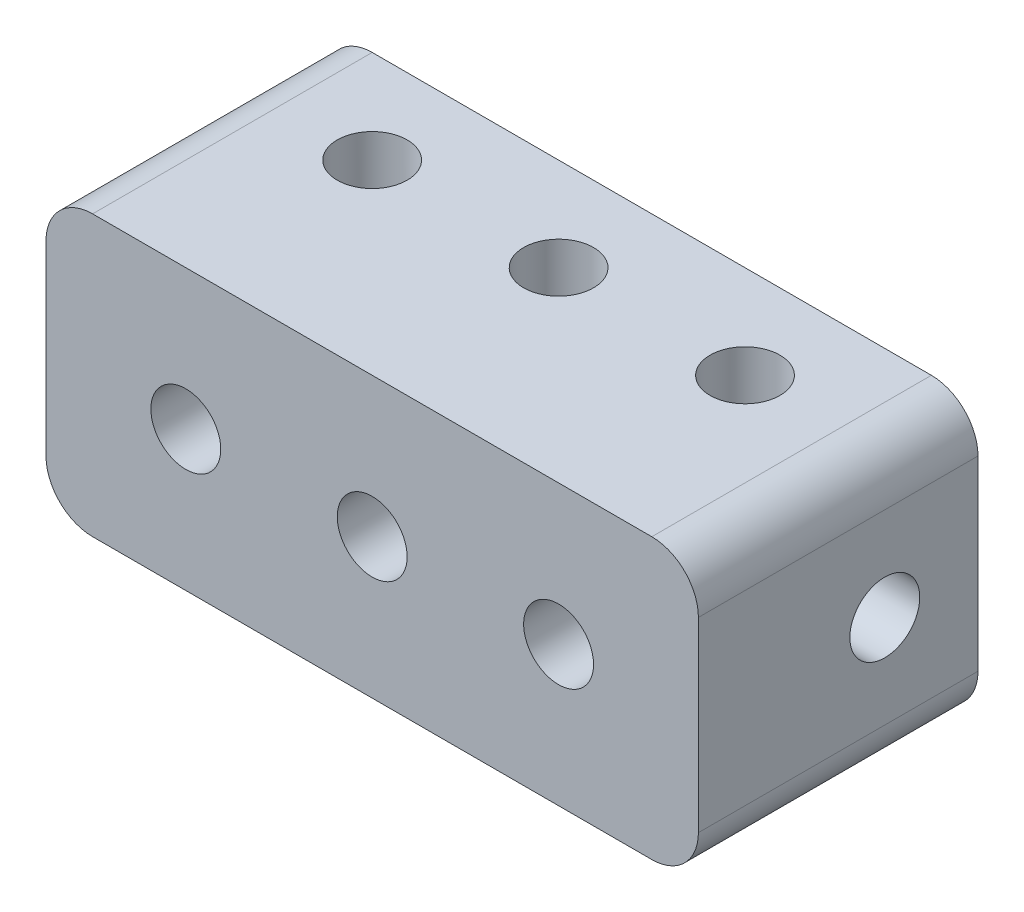
SolidWorks part; units mm, degrees
ref_plane "Front Plane" through (0, 0, 0) normal (0, 0, 1) x (1, 0, 0)
ref_plane "Top Plane" through (0, 0, 0) normal (0, 1, 0) x (1, 0, 0)
ref_plane "Right Plane" through (0, 0, 0) normal (1, 0, 0) x (0, 0, -1)
sketch "Sketch2" plane through (0, 0, 0) normal (0, 0, 1) x (1, 0, 0)
  line L1 (3.175, 0) -> (41.275, 0)
  line L2 (0, 3.175) -> (0, 15.875)
  line L3 (3.175, 19.05) -> (41.275, 19.05)
  line L4 (44.45, 3.175) -> (44.45, 15.875)
  arc A0 (0, 15.875) -> (3.175, 19.05) centre (3.175, 15.875) cw
  arc A1 (41.275, 19.05) -> (44.45, 15.875) centre (41.275, 15.875) cw
  arc A2 (3.175, 0) -> (0, 3.175) centre (3.175, 3.175) cw
  arc A3 (41.275, 0) -> (44.45, 3.175) centre (41.275, 3.175) ccw
  point P7 (0, 19.05)
  point P10 (44.45, 19.05)
  point P13 (0, 0)
  point P16 (44.45, 0)
  dimension "D3" = 3.175
  dimension "D4" = 3.175
  dimension "D5" = 3.175
  dimension "D6" = 3.175
  dimension "D1" = 44.45
  dimension "D2" = 19.05
extrude "Boss-Extrude1" add sketch "Sketch2" along normal blind 19.05
sketch "Sketch3" plane through (0, 0, 0) normal (0, 0, -1) x (-1, 0, 0)
  line L0 (-34.925, 9.525) -> (-9.525, 9.525) construction
  line L1 (-34.925, 14.2875) -> (-9.525, 14.2875)
  line L2 (-34.925, 4.7625) -> (-9.525, 4.7625)
  line L3 (-41.275, 19.05) -> (-3.175, 19.05) construction
  line L4 (-3.175, 0) -> (-41.275, 0) construction
  line L6 (0, 15.875) -> (0, 3.175) construction
  line L7 (-44.45, 3.175) -> (-44.45, 15.875) construction
  arc A0 (-34.925, 14.2875) -> (-34.925, 4.7625) centre (-34.925, 9.525) ccw
  arc A1 (-9.525, 4.7625) -> (-9.525, 14.2875) centre (-9.525, 9.525) ccw
  point P2 (-22.225, 9.525)
  dimension "D3" = 9.525
  dimension "D4" = 9.525
  dimension "D1" = 4.7625
  dimension "D2" = 4.7625
extrude "Cut-Extrude1" cut sketch "Sketch3" against normal blind 14.1224
sketch "Sketch4" plane through (0, 19.05, 0) normal (0, 1, 0) x (1, 0, 0)
  line L0 (44.45, -19.05) -> (44.45, 0) construction
  line L1 (41.275, -19.05) -> (3.175, -19.05) construction
  line L2 (0, -19.05) -> (0, 0) construction
  circle A0 centre (34.925, -6.35) radius 2.3812
  circle A1 centre (22.225, -6.35) radius 2.3813
  circle A2 centre (9.525, -6.35) radius 2.3812
  dimension "D1" = 9.525
  dimension "D2" = 12.7
  dimension "D3" = 4.7625
  dimension "D4" = 4.7625
  dimension "D5" = 4.7625
  dimension "D6" = 9.525
  dimension "D7" = 12.7
  dimension "D8" = 12.7
  dimension "D9" = 12.7
extrude "Cut-Extrude2" cut sketch "Sketch4" against normal through all both and the other way through all
sketch "Sketch5" plane through (44.45, 0, 0) normal (1, 0, 0) x (0, 0, -1)
  line L0 (0, 3.175) -> (0, 15.875) construction
  line L1 (-19.05, 0) -> (0, 0) construction
  circle A0 centre (-6.35, 9.525) radius 2.3813
  dimension "D1" = 6.35
  dimension "D2" = 4.7625
  dimension "D3" = 9.525
extrude "Cut-Extrude3" cut sketch "Sketch5" against normal through all both and the other way through all
sketch "Sketch7" plane through (0, 0, 19.05) normal (0, 0, 1) x (1, 0, 0)
  line L0 (44.45, 3.175) -> (44.45, 15.875) construction
  line L1 (0, 15.875) -> (0, 3.175) construction
  line L2 (3.175, 0) -> (41.275, 0) construction
  circle A0 centre (22.225, 9.525) radius 2.3813
  circle A1 centre (34.925, 9.525) radius 2.3812
  circle A2 centre (9.525, 9.525) radius 2.3813
  dimension "D1" = 4.7625
  dimension "D2" = 4.7625
  dimension "D3" = 4.7625
  dimension "D4" = 12.7
  dimension "D6" = 9.525
  dimension "D7" = 9.525
  dimension "D8" = 9.525
  dimension "D9" = 9.525
  dimension "D5" = 12.7
extrude "Cut-Extrude4" cut sketch "Sketch7" against normal through all both and the other way through all
